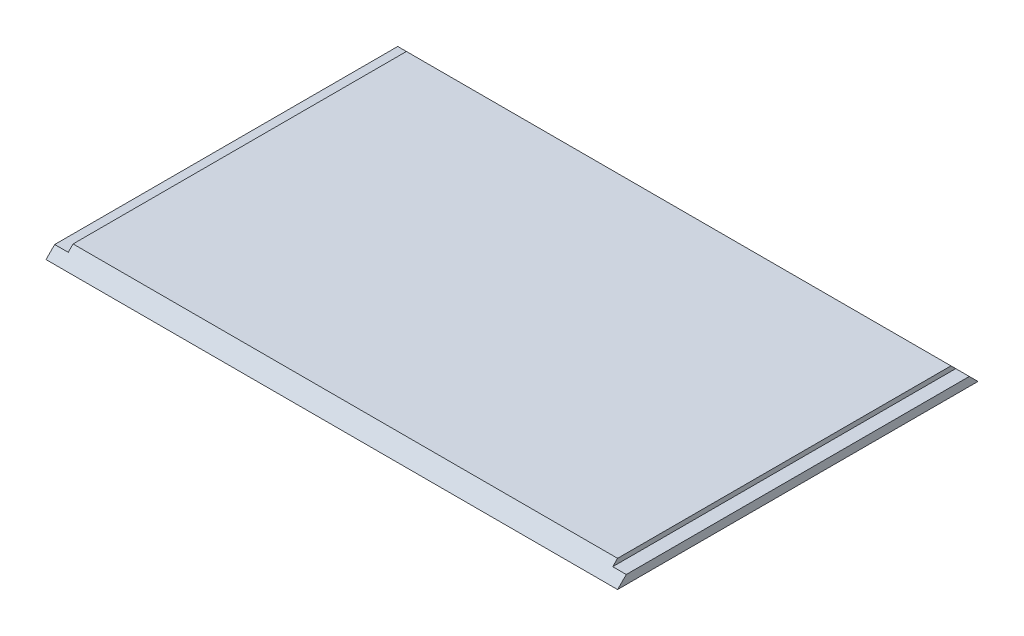
SolidWorks part; units mm, degrees
material "柚木"
ref_plane "前视基准面" through (0, 0, 0) normal (0, 0, 1) x (1, 0, 0)
ref_plane "上视基准面" through (0, 0, 0) normal (0, 1, 0) x (1, 0, 0)
ref_plane "右视基准面" through (0, 0, 0) normal (1, 0, 0) x (0, 0, -1)
sketch "草图1" plane through (0, 0, 0) normal (0, 1, 0) x (1, 0, 0)
  line L1 (-52.0051, 22.6058) -> (66.2949, 22.6058)
  line L2 (-52.0051, 22.6058) -> (-52.0051, -51.9942)
  line L3 (-52.0051, -51.9942) -> (66.2949, -51.9942)
  line L4 (66.2949, 22.6058) -> (66.2949, -51.9942)
  dimension "D1" = 118.3
  dimension "D2" = 74.6
extrude "凸台-拉伸1" add sketch "草图1" along normal blind 2.8
sketch "草图2" plane through (0, 2.8, 0) normal (0, 1, 0) x (1, 0, 0)
  line L0 (-52.0051, -51.9942) -> (66.2949, -51.9942) construction
  line L1 (66.2949, 22.6058) -> (63.4949, 22.6058)
  line L2 (66.2949, 22.6058) -> (66.2949, -51.9942)
  line L3 (66.2949, -51.9942) -> (63.4949, -51.9942)
  line L4 (63.4949, 22.6058) -> (63.4949, -51.9942)
  line L6 (-52.0051, 22.6058) -> (-49.2051, 22.6058)
  line L7 (-52.0051, 22.6058) -> (-52.0051, -51.9942)
  line L8 (-52.0051, -51.9942) -> (-49.2051, -51.9942)
  line L9 (-49.2051, 22.6058) -> (-49.2051, -51.9942)
  dimension "D1" = 2.8
  dimension "D2" = 2.8
extrude "切除-拉伸1" cut sketch "草图2" against normal blind 1
sketch "草图3" plane through (66.2949, 0, 0) normal (1, 0, 0) x (0, 0, -1)
  line L0 (-51.9942, 0) -> (-49.1942, 2.8)
  line L1 (22.6058, 2.8) -> (-51.9942, 2.8) construction
  line L2 (-49.1942, 2.8) -> (-51.9942, 2.8)
  line L3 (-51.9942, 2.8) -> (-51.9942, 0)
  line L4 (22.6058, 0) -> (19.8058, 2.8)
  line L5 (19.8058, 2.8) -> (22.6058, 2.8)
  line L6 (22.6058, 2.8) -> (22.6058, 0)
  dimension "D1" = 45
  dimension "D2" = 45
extrude "切除-拉伸2" cut sketch "草图3" against normal through all
